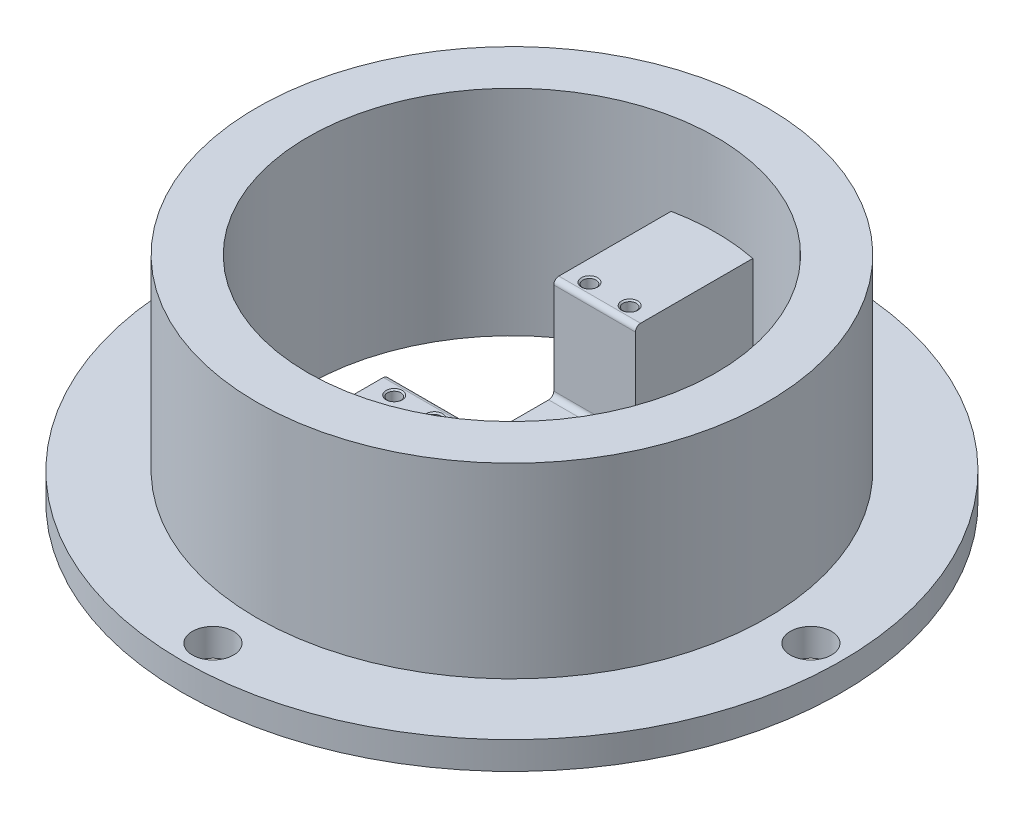
SolidWorks part; units mm, degrees
other "Markup1"
sketch "Sketch12"
other "Markup2"
sketch "Sketch13" plane through (82.0154, 38.1, 82.0154) normal (0.6955, 0.6299, 0.3456) x (0.7099, -0.5282, -0.466)
ref_plane "Front Plane" through (0, 0, 0) normal (0, 0, 1) x (1, 0, 0)
ref_plane "Top Plane" through (0, 0, 0) normal (0, 1, 0) x (1, 0, 0)
ref_plane "Right Plane" through (0, 0, 0) normal (1, 0, 0) x (0, 0, -1)
sketch "Sketch2" plane through (0, 0, 0) normal (0, 1, 0) x (1, 0, 0)
  circle A0 centre (0, 0) radius 63.5
  circle A1 centre (0, 0) radius 50.8
  dimension "D1" = 127
  dimension "D2" = 101.6
extrude "Boss-Extrude1" add sketch "Sketch2" along normal blind 53.34 contours A1 | A0
sketch "Sketch4" plane through (0, 0, 0) normal (0, 1, 0) x (1, 0, 0)
  circle A0 centre (0, 0) radius 82.0154
extrude "Boss-Extrude3" add sketch "Sketch4" along normal blind 6.858 contours A0
sketch "Sketch6" plane through (0, 6.858, 0) normal (0, 1, 0) x (1, 0, 0)
  line L0 (-82.0154, 0) -> (82.0154, 0) construction
  line L1 (-55, 0) -> (55, 0) construction
  line L2 (0, 82.0154) -> (0, -82.0154) construction
  circle A0 centre (0, 0) radius 82.0154 construction
  circle A1 centre (0, 74.3954) radius 5.1215
  circle A2 centre (-74.6494, 0) radius 5.1215
  circle A3 centre (74.3954, 0) radius 5.1215
  circle A4 centre (0, -74.3954) radius 5.1215
  dimension "D1" = 7.62
  dimension "D2" = 7.62
  dimension "D3" = 7.366
  dimension "D4" = 7.62
extrude "Cut-Extrude2" cut sketch "Sketch6" against normal through all both and the other way through all
sketch "Sketch8" plane through (0, 6.858, 0) normal (0, 1, 0) x (1, 0, 0)
  line L0 (0, 73.8288) -> (0, -74.3954) construction
  line L1 (-10.16, 49.7736) -> (-10.16, -49.7736)
  line L3 (10.16, 49.7736) -> (10.16, -49.7736)
  circle A0 centre (0, 0) radius 50.8 construction
  arc A1 (-10.16, 49.7736) -> (-10.16, -49.7736) centre (0, 0) ccw
  arc A2 (10.16, -49.7736) -> (10.16, 49.7736) centre (0, 0) ccw
  dimension "D1" = 10.16
  dimension "D2" = 10.16
extrude "Cut-Extrude3" cut sketch "Sketch8" against normal through all both and the other way through all
sketch "Sketch9" plane through (0, 6.858, 0) normal (0, 1, 0) x (1, 0, 0)
  line L0 (-10.16, 11.43) -> (10.16, 11.43)
  line L1 (-10.16, 11.43) -> (-10.16, 49.9059)
  line L2 (-10.16, -49.7736) -> (-10.16, 49.7736) construction
  line L3 (-10.16, 0) -> (10.16, 0) construction
  line L4 (10.16, 49.7736) -> (10.16, -49.7736) construction
  line L5 (-10.16, 11.43) -> (10.16, 11.43)
  line L6 (-10.16, -11.43) -> (10.16, -11.43)
  line L7 (10.16, 11.43) -> (10.16, -49.7736)
  line L8 (-10.16, -49.7736) -> (-10.16, 11.43)
  line L9 (-10.16, -49.7736) -> (-10.16, -11.43)
  line L10 (10.16, 11.43) -> (10.16, 49.9059)
  line L11 (-10.16, 49.9059) -> (10.16, 49.9059)
  line L12 (-10.16, 49.9059) -> (-10.16, 49.7736)
  line L13 (-10.16, 49.7736) -> (0, 50.8)
  line L14 (0, 50.8) -> (10.16, 49.7736)
  line L15 (10.16, 49.7736) -> (10.16, 49.9059)
  line L18 (-10.16, 49.7736) -> (-10.16, -49.7736)
  line L19 (-10.16, 49.7736) -> (-10.16, -49.7736)
  line L22 (10.16, -49.7736) -> (10.16, 49.7736)
  line L23 (10.16, -49.7736) -> (10.16, 49.7736)
  arc A0 (10.16, 49.7736) -> (-10.16, 49.7736) centre (0, 0) ccw construction
  arc A2 (-10.16, -49.7736) -> (10.16, -49.7736) centre (0, 0) ccw
  arc A8 (-10.16, -49.7736) -> (10.16, -49.7736) centre (0, 0) ccw
  arc A9 (10.16, 49.7736) -> (-10.16, 49.7736) centre (0, 0) ccw
  arc A10 (10.16, 49.7736) -> (-10.16, 49.7736) centre (0, 0) ccw
  dimension "D1" = 11.43
  dimension "D2" = 11.43
  dimension "D3" = 0
extrude "Boss-Extrude4" add sketch "Sketch9" along normal blind 25.908 contours L0 L1 L11 L10 | L19 A8 L23 A10
sketch "Sketch11" plane through (0, 32.766, 0) normal (0, 1, 0) x (1, 0, 0)
  line L0 (-10.16, 0) -> (10.16, 0) construction
  line L1 (-10.16, -49.7736) -> (-10.16, 49.7736) construction
  line L2 (10.16, -49.7736) -> (10.16, 49.7736) construction
  line L3 (-10.16, 20.574) -> (10.16, 20.574)
  line L4 (-10.16, -20.574) -> (10.16, -20.574)
  line L7 (-10.16, -20.574) -> (-10.16, 20.574)
  line L9 (10.16, -20.574) -> (10.16, 20.574)
  line L10 (-10.16, -20.574) -> (10.16, 20.574) construction
  line L11 (-10.16, 20.574) -> (10.16, -20.574) construction
  point P10 (0, 0)
  dimension "D1" = 20.574
  dimension "D2" = 20.574
extrude "Cut-Extrude5" cut sketch "Sketch11" against normal blind 25.4 and the other way through all
fillet "Fillet1" radius 1.27 4 edges at (0, 7.366, 20.574) (0, 32.766, 20.574) (0, 32.766, -20.574) (0, 7.366, -20.574)
sketch "Sketch14" plane through (0, 32.766, 0) normal (0, 1, 0) x (1, 0, 0)
  circle A0 centre (5, -24.3) radius 2.2
  circle A1 centre (-5, -24.3) radius 2.2
  circle A2 centre (5, 24.3) radius 2
  circle A3 centre (-5, 24.3) radius 2
  point P0 (5, -24.3)
  point P2 (-5, -24.3)
  point P4 (5, 24.3)
  point P6 (-5, 24.3)
  point P17 (-5, -24.3)
  point P19 (5, -24.3)
  dimension "D1" = 4
hole_wizard "M4x0.7 Tapped Hole3" positions "Sketch14" profile "Sketch15" tap size "M4x0.7" standard "ANSI Metric"
sketch "Sketch15" plane through (5, 32.766, 24.3) normal (1, 0, 0) x (0, 0, 1)
  line L0 (0, 0) -> (0, 10.8974)
  line L1 (0, 10.8974) -> (1.65, 9.906)
  line L2 (1.65, 9.906) -> (1.65, 0.3147)
  line L3 (1.65, 0.3147) -> (2.025, 0)
  line L5 (2.025, 0) -> (0, 0)
  line L6 (-1.65, 0.3147) -> (-2.025, 0) construction
  line L10 (0, 10.8974) -> (-1.65, 9.906) construction
  line L11 (0, -6.35) -> (0, 107.95) construction
  dimension "Tap Drill Dia." = 3.3
  dimension "Tap Drill Depth" = 9.906
  dimension "Near C'Sink Dia." = 4.05
  dimension "Near C'Sink Angle" = 100
  dimension "Drill Angle" = 118
cosmetic thread "Hole Thread3" parameters "D1"=7.874, "D2"=4
cosmetic thread "Hole Thread4" parameters "D1"=7.874, "D2"=4
cosmetic thread "Hole Thread5" parameters "D1"=7.874, "D2"=4
cosmetic thread "Hole Thread6" parameters "D1"=7.874, "D2"=4
